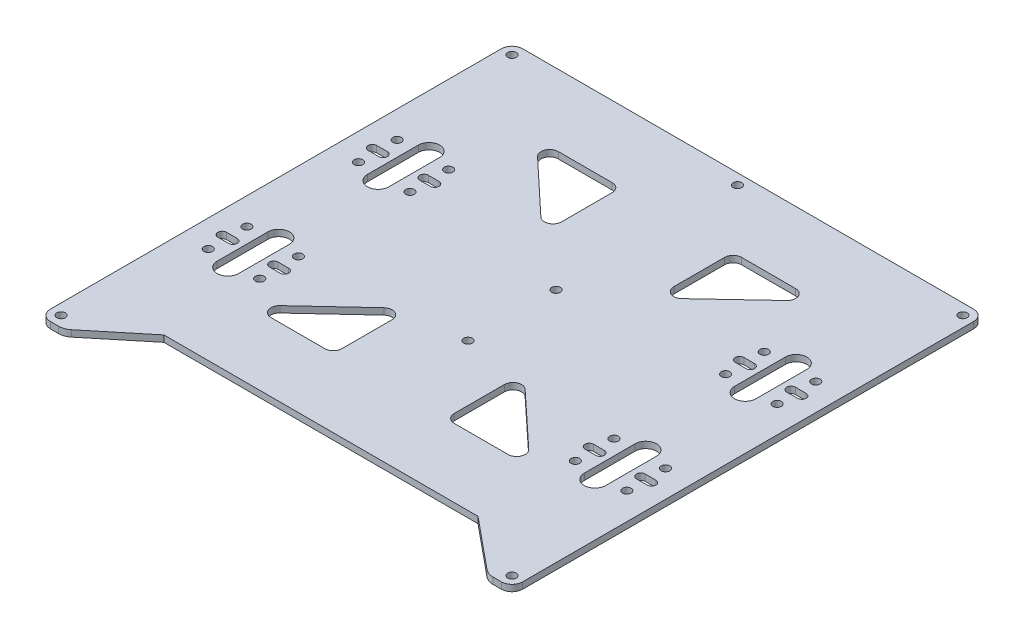
SolidWorks part; units mm, degrees
ref_plane "Front Plane" through (0, 0, 0) normal (0, 0, 1) x (1, 0, 0)
ref_plane "Top Plane" through (0, 0, 0) normal (0, 1, 0) x (1, 0, 0)
ref_plane "Right Plane" through (0, 0, 0) normal (1, 0, 0) x (0, 0, -1)
sketch "Sketch1" plane through (0, 0, 0) normal (0, 1, 0) x (1, 0, 0)
  line L0 (25.5785, 40) -> (25.5785, 76.8339)
  line L1 (25.5785, 76.8339) -> (64.8089, 76.8339)
  line L2 (-1061.5, 0) -> (48938.5, 0) construction
  line L3 (-0.5674, 110) -> (-0.5674, 107)
  line L4 (64.8089, 76.8339) -> (25.5785, 40)
  line L5 (25.5785, -20.5001) -> (25.5785, -57.0616)
  line L6 (109.4326, 105) -> (109.4326, 0)
  line L7 (25.5785, -57.0616) -> (64.8089, -57.0616)
  line L8 (64.8089, -57.0616) -> (25.5785, -20.5001)
  line L9 (-0.5674, 18.5) -> (-0.5674, -18.5)
  line L10 (-0.5674, -22.5) -> (-0.5674, -89)
  line L11 (136.0589, -110) -> (72.5931, -110) construction
  line L12 (-0.5674, 103) -> (-0.5674, 22.5)
  line L13 (-0.5674, -89) -> (72.5931, -89)
  line L14 (84.9326, -23.1649) -> (84.9326, -46.8352) construction
  line L15 (109.4326, 0) -> (109.4326, -105)
  line L16 (89.9326, -23.1649) -> (89.9326, -46.8352)
  line L17 (79.9326, -23.1649) -> (79.9326, -46.8352)
  line L18 (70.4326, -35) -> (75.4326, -35) construction
  line L19 (70.4326, -33) -> (75.4326, -33)
  line L20 (70.4326, -37) -> (75.4326, -37)
  line L21 (94.4326, -35) -> (99.4326, -35) construction
  line L22 (94.4326, -33) -> (99.4326, -33)
  line L23 (94.4326, -37) -> (99.4326, -37)
  line L24 (84.9326, 23.1648) -> (84.9326, 46.8351) construction
  line L25 (89.9326, 23.1648) -> (89.9326, 46.8351)
  line L26 (79.9326, 23.1648) -> (79.9326, 46.8351)
  line L27 (70.4326, 35) -> (75.4326, 35) construction
  line L28 (70.4326, 33) -> (75.4326, 33)
  line L29 (70.4326, 37) -> (75.4326, 37)
  line L30 (96.2056, -108.4078) -> (72.5931, -89)
  line L31 (94.4326, 35) -> (99.4326, 35) construction
  line L32 (94.4326, 33) -> (99.4326, 33)
  line L33 (94.4326, 37) -> (99.4326, 37)
  line L34 (100.6504, -110) -> (104.4326, -110)
  line L44 (104.4326, 110) -> (-0.5674, 110)
  arc A0 (-0.5674, 103) -> (-0.5674, 107) centre (-0.5674, 105) ccw
  arc A1 (-0.5674, 18.5) -> (-0.5674, 22.5) centre (-0.5674, 20.5) ccw
  arc A2 (89.9326, -23.1649) -> (79.9326, -23.1649) centre (84.9326, -23.1649) ccw
  arc A3 (-0.5674, -18.5) -> (-0.5674, -22.5) centre (-0.5674, -20.5) cw
  arc A4 (79.9326, -46.8352) -> (89.9326, -46.8352) centre (84.9326, -46.8352) ccw
  circle A5 centre (104.4326, 105) radius 2
  circle A6 centre (104.4326, -105) radius 2
  arc A7 (104.4326, -110) -> (109.4326, -105) centre (104.4326, -105) ccw
  arc A8 (109.4326, 105) -> (104.4326, 110) centre (104.4326, 105) ccw
  arc A9 (70.4326, -33) -> (70.4326, -37) centre (70.4326, -35) ccw
  arc A10 (75.4326, -37) -> (75.4326, -33) centre (75.4326, -35) ccw
  arc A11 (94.4326, -33) -> (94.4326, -37) centre (94.4326, -35) ccw
  arc A12 (99.4326, -37) -> (99.4326, -33) centre (99.4326, -35) ccw
  arc A13 (89.9326, 23.1648) -> (79.9326, 23.1648) centre (84.9326, 23.1648) cw
  arc A14 (79.9326, 46.8351) -> (89.9326, 46.8351) centre (84.9326, 46.8351) cw
  arc A15 (70.4326, 33) -> (70.4326, 37) centre (70.4326, 35) cw
  arc A16 (75.4326, 37) -> (75.4326, 33) centre (75.4326, 35) cw
  arc A17 (94.4326, 33) -> (94.4326, 37) centre (94.4326, 35) cw
  arc A18 (99.4326, 37) -> (99.4326, 33) centre (99.4326, 35) cw
  circle A19 centre (96.9326, 26) radius 2
  circle A20 centre (72.9326, 26) radius 2
  circle A21 centre (72.9326, 44) radius 2
  circle A22 centre (96.9326, -44) radius 2
  circle A23 centre (72.9326, -44) radius 2
  circle A24 centre (72.9326, -26) radius 2
  circle A25 centre (96.9326, -26) radius 2
  circle A26 centre (96.9326, 44) radius 2
  arc A27 (100.6504, -110) -> (96.2056, -108.4078) centre (100.6504, -103) cw
  point P27 (84.9326, -35)
  point P35 (72.9326, -35)
  point P47 (96.9326, -35)
  point P59 (84.9326, 35)
  point P69 (72.9326, 35)
  point P78 (96.9326, 35)
  point P92 (98.1428, -110)
  dimension "D4" = 18
  dimension "D1" = 2
  dimension "D2" = 12.5
  dimension "D14" = 12
  dimension "D15" = 2
  dimension "D18" = 5
  dimension "D16" = 7
  dimension "D3" = 24
  dimension "D5" = 5
  dimension "D6" = 110
  dimension "D8" = 41
  dimension "D10" = 220
  dimension "D11" = 89
  dimension "D12" = 110
  dimension "D17" = 5
  dimension "D19" = 9
extrude "Boss-Extrude2" add sketch "Sketch1" along normal blind 3
fillet "Fillet1" radius 4 6 edges at (64.8089, 1.5, 57.0616) (25.5785, 1.5, 57.0616) (25.5785, 1.5, 20.5001) (25.5785, 1.5, -40) (25.5785, 1.5, -76.8339) (64.8089, 1.5, -76.8339)
mirror "Mirror1" about plane through (-0.5674, 3, -103) normal (1, 0, 0) of "Boss-Extrude2", "Fillet1"
sketch "Sketch2" plane through (0, 3, 0) normal (0, 1, 0) x (1, 0, 0)
